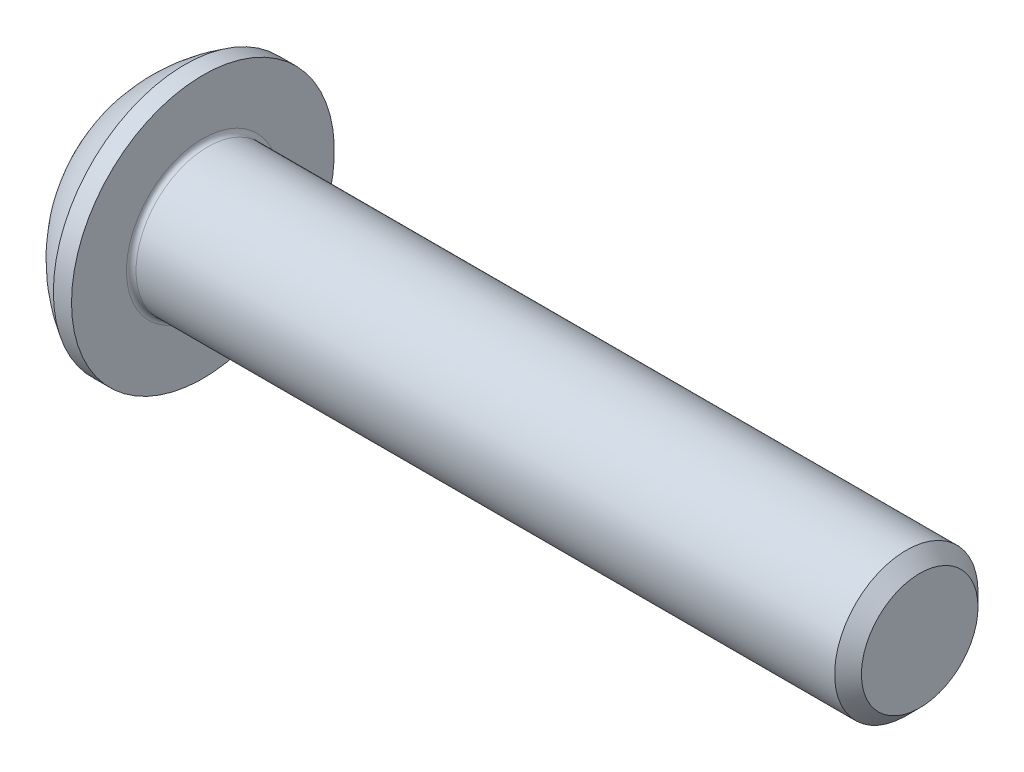
SolidWorks part; units mm, degrees
ref_plane "Front Plane" through (0, 0, 0) normal (0, 0, 1) x (1, 0, 0)
ref_plane "Top Plane" through (0, 0, 0) normal (0, 1, 0) x (1, 0, 0)
ref_plane "Right Plane" through (0, 0, 0) normal (1, 0, 0) x (0, 0, -1)
ref_plane "Plane1" through (0, 0, 0) normal (0, 0, -1) x (-1, 0, 0)
sketch "Sketch1" plane through (0, 0, 0) normal (0, 0, -1) x (-1, 0, 0)
  line L0 (-1.65, 2.75) -> (-1.65, 0)
  line L1 (-1.65, 0) -> (0, 0)
  line L2 (0, 0) -> (0, 1.425)
  line L3 (-1.27, 2.75) -> (-1.65, 2.75)
  line L4 (-1.65, 0) -> (0, 0) construction
  arc A0 (0, 1.425) -> (-1.27, 2.75) centre (-2.962, -0.1429) ccw
  point P6 (0, 0)
  dimension "D5" = 3.3514
  dimension "D1" = 2.75
  dimension "D2" = 1.65
  dimension "D3" = 1.425
  dimension "D4" = 0.38
revolve "Revolve1" add sketch "Sketch1" angle 360 about L4
sketch "Sketch2" plane through (0, 0, 0) normal (-1, 0, 0) x (0, 0, 1)
  line L7 (-1, 0.5774) -> (-1, -0.5774)
  line L8 (-1, -0.5774) -> (0, -1.1547)
  line L9 (0, -1.1547) -> (1, -0.5774)
  line L10 (1, -0.5774) -> (1, 0.5774)
  line L11 (1, 0.5774) -> (0, 1.1547)
  line L12 (0, 1.1547) -> (-1, 0.5774)
  circle A0 centre (0, 0) radius 1 construction
  point P7 (0, 0)
  point P10 (0, 0)
  dimension "D1" = 2
extrude "Cut-Extrude1" cut sketch "Sketch2" against normal blind 1.04
sketch "Sketch3" plane through (0, 0, 0) normal (0, 0, 1) x (1, 0, 0)
  line L0 (1.04, 1) -> (1.04, 0)
  line L1 (1.04, 0) -> (1.6174, 0)
  line L2 (1.6174, 0) -> (1.04, 1)
  line L3 (1.04, 0) -> (1.6174, 0) construction
revolve "Cut-Revolve1" cut sketch "Sketch3" angle 360 about L3
sketch "Sketch4" plane through (1.65, 0, 0) normal (1, 0, 0) x (0, 0, -1)
  circle A0 centre (0, 0) radius 1.5
extrude "Largo y Ancho rosca" add sketch "Sketch4" along normal blind 15
fillet "Fillet1" radius 0.1 1 edges at (1.65, 0, -1.5)
chamfer "Chamfer1" distance 0.2805 angle 45 1 edges at (16.65, 0, -1.5)
